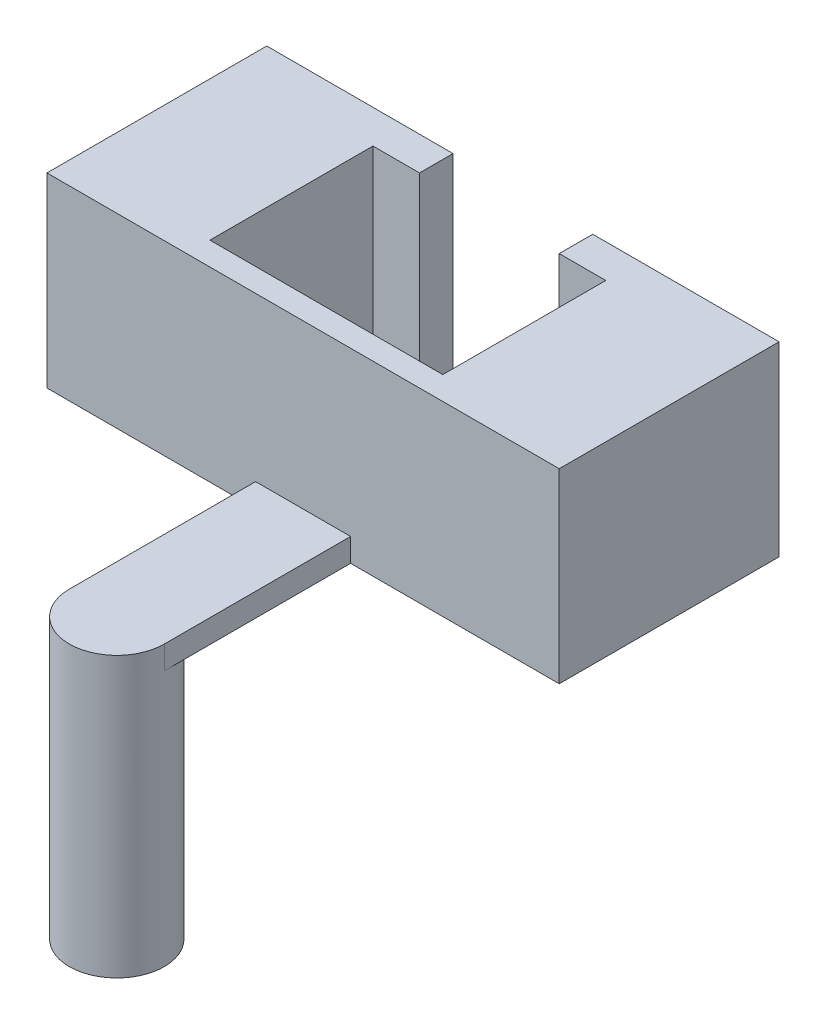
SolidWorks part; units mm, degrees
ref_plane "Front Plane" through (0, 0, 0) normal (0, 0, 1) x (1, 0, 0)
ref_plane "Top Plane" through (0, 0, 0) normal (0, 1, 0) x (1, 0, 0)
ref_plane "Right Plane" through (0, 0, 0) normal (1, 0, 0) x (0, 0, -1)
sketch "Sketch1" plane through (0, 0, 0) normal (0, 1, 0) x (1, 0, 0)
  circle A0 centre (-1.7341, 7.7072) radius 12.954
  dimension "D1" = 25.908
extrude "Boss-Extrude1" add sketch "Sketch1" along normal blind 76.2 contours A0
sketch "Sketch3" plane through (0, 76.2, 0) normal (0, 1, 0) x (1, 0, 0)
  line L1 (-14.6881, 7.7072) -> (11.2199, 7.7072)
  line L2 (-14.6881, 7.7072) -> (-14.6881, 58.5072)
  line L3 (-14.6881, 58.5072) -> (11.2199, 58.5072)
  line L4 (11.2199, 7.7072) -> (11.2199, 58.5072)
  circle A0 centre (-1.7341, 7.7072) radius 12.954 construction
  dimension "D1" = 50.8
  dimension "D2" = 25.908
extrude "Boss-Extrude3" add sketch "Sketch3" against normal blind 6.35
sketch "Sketch7" plane through (0, 0, -58.5072) normal (0, 0, -1) x (-1, 0, 0)
  line L0 (-11.2199, 69.85) -> (14.6881, 69.85) construction
  line L1 (-30.0159, 120.65) -> (33.4841, 120.65)
  line L2 (-30.0159, 120.65) -> (-30.0159, 69.85)
  line L3 (-30.0159, 69.85) -> (33.4841, 69.85)
  line L4 (33.4841, 120.65) -> (33.4841, 69.85)
  point P6 (1.7341, 69.85)
  point P7 (1.7341, 69.85)
  dimension "D1" = 50.8
  dimension "D2" = 63.5
extrude "Boss-Extrude4" add sketch "Sketch7" along normal blind 6.35
sketch "Sketch10" plane through (0, 69.85, 0) normal (0, -1, 0) x (1, 0, 0)
  line L1 (-33.4841, -58.5072) -> (-71.5841, -58.5072)
  line L2 (-33.4841, -58.5072) -> (-33.4841, -109.3072)
  line L3 (-33.4841, -109.3072) -> (-71.5841, -109.3072)
  line L4 (-71.5841, -58.5072) -> (-71.5841, -109.3072)
  line L5 (30.0159, -58.5072) -> (68.1159, -58.5072)
  line L6 (30.0159, -58.5072) -> (30.0159, -109.3072)
  line L7 (30.0159, -109.3072) -> (68.1159, -109.3072)
  line L8 (68.1159, -58.5072) -> (68.1159, -109.3072)
  dimension "D1" = 38.1
  dimension "D2" = 50.8
  dimension "D3" = 38.1
  dimension "D4" = 50.8
extrude "Boss-Extrude6" add sketch "Sketch10" against normal blind 50.8
sketch "Sketch11" plane through (0, 0, -109.3072) normal (0, 0, -1) x (-1, 0, 0)
  line L0 (-30.0159, 69.85) -> (33.4841, 69.85) construction
  line L1 (-68.1159, 120.65) -> (-17.3159, 120.65)
  line L2 (-68.1159, 120.65) -> (-68.1159, 69.85)
  line L3 (-68.1159, 69.85) -> (-17.3159, 69.85)
  line L4 (-17.3159, 120.65) -> (-17.3159, 69.85)
  line L6 (71.5841, 120.65) -> (20.7841, 120.65)
  line L7 (71.5841, 120.65) -> (71.5841, 69.85)
  line L8 (71.5841, 69.85) -> (20.7841, 69.85)
  line L9 (20.7841, 120.65) -> (20.7841, 69.85)
  dimension "D1" = 50.8
  dimension "D2" = 50.8
extrude "Boss-Extrude7" add sketch "Sketch11" along normal blind 9.144
equation "\"F\"= 600'lbf"
equation "\"P\"= \"F\" / 2 'lbf"
equation "\"P_DE\"= \"P\" / 2'lbf"
equation "\"SF\"= 4"
equation "\"Sy\"= 35000'psi"
equation "\"E\"= 10000000'psi"
equation "\"def\"= 0.005in "
equation "\"Sigma_allow\"= \"Sy\" / \"SF\"'psi"
equation "\"LA\"= 3in"
equation "\"DA\"= ( ( 64 * \"P\" * ( \"LA\" ) ^ 3 ) / ( 3 * PI * \"E\" * \"def\" ) ) ^ ( 1 / 4 ) "
equation "\"LB\"= \"DA\""
equation "\"hB\"= 2in"
equation "\"tB\"= 0.250in "
equation "\"LC\"= 2.5in"
equation "\"tC\"= 2in"
equation "\"hC\"= 0.2535in "
equation "\"LD\"= 1.498in"
equation "\"hD\"= 2in"
equation "\"tD\"= 0.25in"
equation "\"LE\"= 2in"
equation "\"tE\"= \"DA\""
equation "\"hE\"= ( ( 4 * \"P_DE\" * \"LE\" ^ 3 ) / ( \"E\" * \"tE\" * \"def\" ) ) ^ ( 1 / 3 )"
